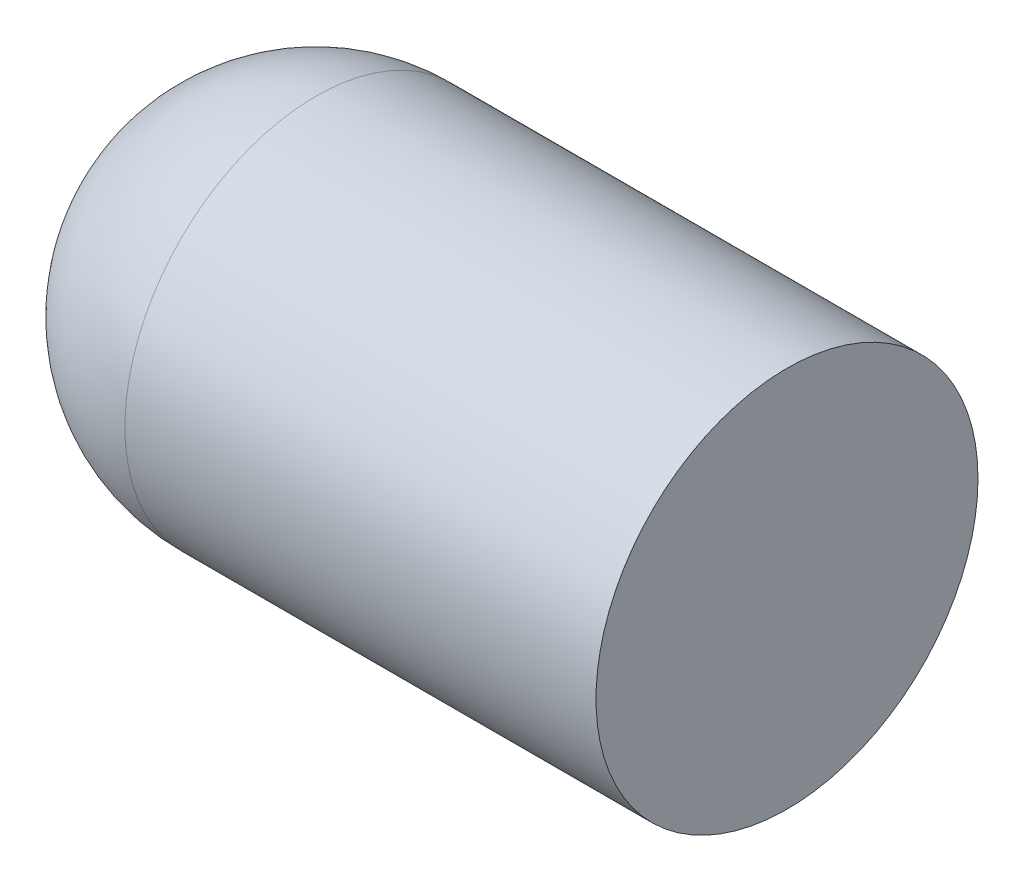
SolidWorks part; units mm, degrees
ref_plane "Front Plane" through (0, 0, 0) normal (0, 0, 1) x (1, 0, 0)
ref_plane "Top Plane" through (0, 0, 0) normal (0, 1, 0) x (1, 0, 0)
ref_plane "Right Plane" through (0, 0, 0) normal (1, 0, 0) x (0, 0, -1)
sketch "Sketch1" plane through (0, 0, 0) normal (1, 0, 0) x (0, 0, -1)
  line L0 (0, -1.5) -> (0, 1.5)
  arc A0 (0, 1.5) -> (0, -1.5) centre (0, 0) cw
  point P4 (0, 7.2764)
  point P5 (0, 0)
  dimension "D1" = 3
revolve "Revolve1" add sketch "Sketch1" angle 180 about L0
sketch "Sketch2" plane through (0, 0, 0) normal (1, 0, 0) x (0, 0, -1)
  circle A0 centre (0, 0) radius 1.5
extrude "Boss-Extrude1" add sketch "Sketch2" along normal blind 3.7
